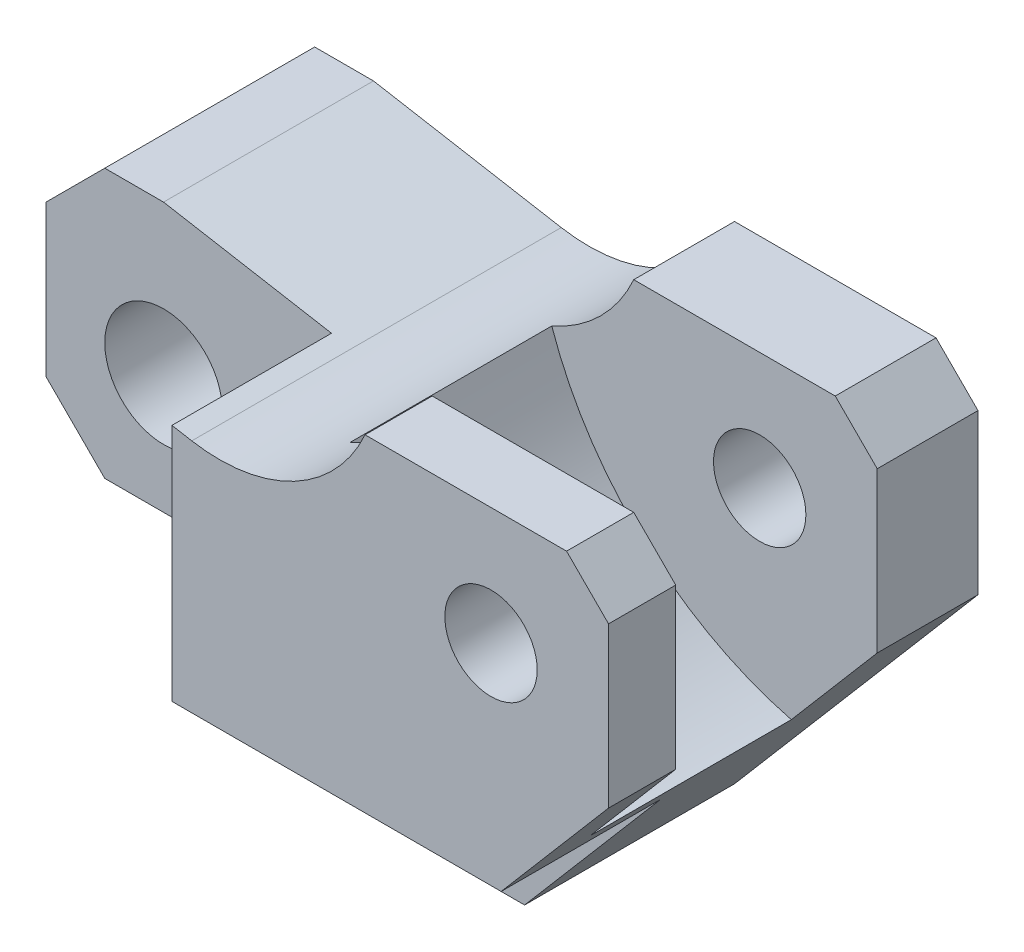
SolidWorks part; units mm, degrees
material "AISI 1020"
ref_plane "Front Plane" through (0, 0, 0) normal (0, 0, 1) x (1, 0, 0)
ref_plane "Top Plane" through (0, 0, 0) normal (0, 1, 0) x (1, 0, 0)
ref_plane "Right Plane" through (0, 0, 0) normal (1, 0, 0) x (0, 0, -1)
sketch "Sketch1" plane through (0, 0, 0) normal (0, 0, 1) x (1, 0, 0)
  line L0 (0, 7) -> (0, 25)
  line L1 (7, 32) -> (14, 32)
  line L2 (14, 32) -> (36.3614, 28.0571)
  line L3 (57, 39) -> (81, 39)
  line L4 (86, 34) -> (86, 15)
  line L5 (86, 15) -> (57, -19)
  line L6 (57, -19) -> (51.297, -19)
  line L7 (39.5755, 0) -> (7, 0)
  line L8 (0, 25) -> (7, 32)
  line L9 (7, 0) -> (0, 7)
  line L10 (81, 39) -> (86, 34)
  arc A0 (36.3614, 28.0571) -> (57, 39) centre (39.6607, 46.7684) ccw
  arc A1 (39.5755, 0) -> (44.5212, -4.2647) centre (39.5755, -5) cw
  arc A2 (44.5212, -4.2647) -> (51.297, -19) centre (73.2059, 0) ccw
  circle A3 centre (14, 14) radius 7
  point P0 (0, 0)
  point P1 (0, 32)
  point P9 (86, 39)
  dimension "D8" = 19
  dimension "D15" = 5
  dimension "D16" = 29
  dimension "D19" = 14
  dimension "D1" = 86
  dimension "D2" = 58
  dimension "D3" = 32
  dimension "D4" = 14
  dimension "D5" = 10
  dimension "D9" = 29
  dimension "D10" = 24
  dimension "D11" = 29
  dimension "D12" = 19
  dimension "D14" = 19
  dimension "D17" = 14
  dimension "D18" = 14
extrude "Boss-Extrude1" add sketch "Sketch1" along normal blind 44
ref_plane "Plane1" through (0, 0, 12) normal (0, 0, -1) x (-1, 0, 0)
sketch "Sketch3" plane through (0, 0, 12) normal (0, 0, -1) x (-1, 0, 0)
  line L0 (-86, 15) -> (-86, 34) construction
  line L1 (-57, -19) -> (-86, 15) construction
  line L13 (-14, 32) -> (-36.3614, 28.0571)
  line L14 (-7, 32) -> (-14, 32)
  line L15 (0, 25) -> (-7, 32)
  line L16 (0, 7) -> (0, 25)
  line L17 (-7, 0) -> (0, 7)
  line L18 (-39.5755, 0) -> (-7, 0)
  line L19 (-57, -19) -> (-51.297, -19)
  line L20 (-86, 15) -> (-57, -19)
  line L21 (-86, 34) -> (-86, 15)
  line L22 (-81, 39) -> (-86, 34)
  line L23 (-57, 39) -> (-81, 39)
  line L24 (-14, 32) -> (-36.3614, 28.0571)
  line L25 (-7, 32) -> (-14, 32)
  line L26 (0, 25) -> (-7, 32)
  line L27 (0, 7) -> (0, 25)
  line L28 (-7, 0) -> (0, 7)
  line L29 (-39.5755, 0) -> (-7, 0)
  line L30 (-57, -19) -> (-51.297, -19)
  line L31 (-86, 15) -> (-57, -19)
  line L32 (-86, 34) -> (-86, 15)
  line L33 (-81, 39) -> (-86, 34)
  line L34 (-57, 39) -> (-81, 39)
  circle A0 centre (-86, 42.7019) radius 41
  arc A4 (-39.5755, 0) -> (-44.5212, -4.2647) centre (-39.5755, -5) ccw
  arc A5 (-51.297, -19) -> (-44.5212, -4.2647) centre (-73.2059, 0) ccw
  arc A6 (-57, 39) -> (-36.3614, 28.0571) centre (-39.6607, 46.7684) ccw
  arc A7 (-39.5755, 0) -> (-44.5212, -4.2647) centre (-39.5755, -5) ccw
  arc A8 (-51.297, -19) -> (-44.5212, -4.2647) centre (-73.2059, 0) ccw
  arc A9 (-57, 39) -> (-36.3614, 28.0571) centre (-39.6607, 46.7684) ccw
  point P2 (-75.7647, 3)
  point P3 (-84.2788, 12.9821)
  point P6 (0, 0)
  point P7 (0, 0)
  point P8 (-86, 44)
  dimension "D1" = 82
  dimension "D3" = 36
  dimension "D2" = 0
extrude "Cut-Extrude1" cut sketch "Sketch3" against normal blind 24 contours A0
sketch "Sketch4" plane through (86, 0, 0) normal (1, 0, 0) x (0, 0, -1)
  line L0 (-44, -19) -> (0, -19) construction
  line L1 (-44, -19) -> (-44, 15) construction
  line L2 (-44, -19) -> (0, -19)
  line L3 (-44, -19) -> (-44, 15)
  line L5 (-44, -19) -> (-25, -19)
  line L6 (-44, -19) -> (-44, 0)
  line L7 (-44, 0) -> (-25, 0)
  line L8 (-25, -19) -> (-25, 0)
  dimension "D1" = 19
extrude "Cut-Extrude2" cut sketch "Sketch4" against normal through all contours L2 L8 L7 L3
sketch "Sketch5" plane through (0, 0, 44) normal (0, 0, 1) x (1, 0, 0)
  line L0 (86, 15) -> (86, 34) construction
  line L1 (0, 0) -> (34, 0)
  line L2 (0, 0) -> (0, 32)
  line L3 (0, 32) -> (34, 32)
  line L4 (34, 0) -> (34, 32)
  line L5 (14, 32) -> (7, 32) construction
  line L6 (7, 0) -> (73.2059, 0) construction
  line L7 (0, 25) -> (0, 7) construction
  dimension "D1" = 52
extrude "Cut-Extrude4" cut sketch "Sketch5" against normal blind 19
sketch "Sketch6" plane through (0, 0, 44) normal (0, 0, 1) x (1, 0, 0)
  line L2 (86, 15) -> (86, 34) construction
  line L4 (81, 39) -> (57, 39) construction
  circle A0 centre (72, 25) radius 5.5
  point P6 (53.2316, 24.5917)
  point P9 (0, 0)
  dimension "D1" = 11
  dimension "D2" = 14
  dimension "D3" = 14
extrude "Cut-Extrude5" cut sketch "Sketch6" against normal through all
equation "\"A\" = 86"
equation "\"B\" = 58"
equation "\"C\"= 44"
equation "\"D1@Sketch1\"=\"A\""
equation "\"D2@Sketch1\"=\"B\""
equation "\"D1@Boss-Extrude1\"=\"C\""
